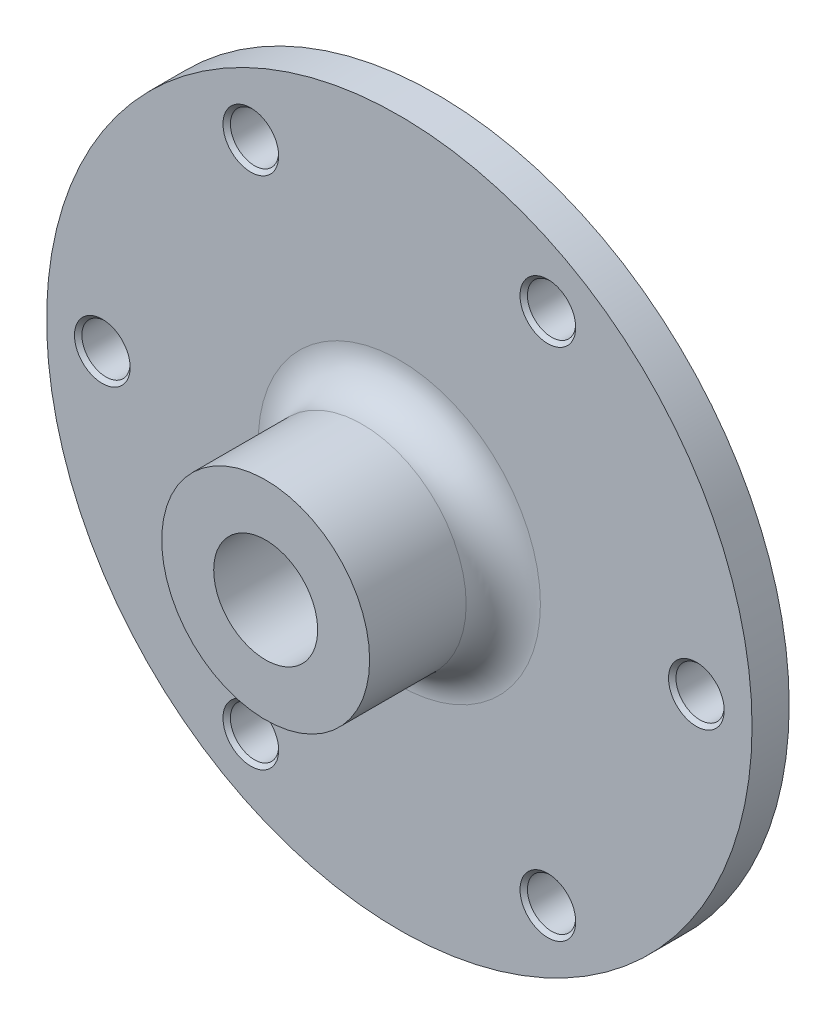
SolidWorks part; units mm, degrees
material "Plain Carbon Steel"
ref_plane "Front Plane" through (0, 0, 0) normal (0, 0, 1) x (1, 0, 0)
ref_plane "Top Plane" through (0, 0, 0) normal (0, 1, 0) x (1, 0, 0)
ref_plane "Right Plane" through (0, 0, 0) normal (1, 0, 0) x (0, 0, -1)
sketch "Sketch1" plane through (0, 0, 0) normal (0, 0, 1) x (1, 0, 0)
  circle A0 centre (0, 0) radius 47.5
  dimension "D1" = 95
extrude "Boss-Extrude1" add sketch "Sketch1" along normal mid plane 5
sketch "Sketch2" plane through (0, 0, -2.5) normal (0, 0, -1) x (-1, 0, 0)
  circle A0 centre (0, 0) radius 35
  dimension "D1" = 70
extrude "Boss-Extrude2" add sketch "Sketch2" along normal blind 5
sketch "Sketch4" plane through (0, 0, 2.5) normal (0, 0, 1) x (1, 0, 0)
  circle A0 centre (0, 0) radius 14
  dimension "D1" = 28
extrude "Boss-Extrude3" add sketch "Sketch4" along normal blind 18
hole_wizard "CSK for M12 Hex Socket Countersunk Cap Screw1" positions "Sketch6" profile "Sketch7" countersink size "M12" standard "ISO" end condition through all
sketch "Sketch6" plane through (0, 0, -7.5) normal (0, 0, -1) x (-1, 0, 0)
  point P0 (0, 0)
sketch "Sketch7" plane through (0, 0, -7.5) normal (1, 0, 0) x (0, 1, 0)
  line L0 (0, 0) -> (0, 28)
  line L1 (0, 28) -> (7, 28)
  line L2 (7, 28) -> (7, 6)
  line L3 (7, 6) -> (13, 0)
  line L5 (13, 0) -> (0, 0)
  line L6 (-7, 6) -> (-13, 0) construction
  line L11 (0, -6.35) -> (0, 107.95) construction
  dimension "Thru Hole Dia." = 14
  dimension "Thru Hole Depth" = 28
  dimension "Near C'Sink Dia." = 26
  dimension "Near C'Sink Angle" = 90
fillet "Fillet1" radius 5 1 edges at (14, 0, 2.5)
sketch "Sketch12" plane through (0, 0, 2.5) normal (0, 0, 1) x (1, 0, 0)
  circle A0 centre (0, 0) radius 40 construction
  dimension "D1" = 80
hole_wizard "CSK for M6 Hex Socket Countersunk Cap Screw1" positions "Sketch13" profile "Sketch14" countersink size "M6" standard "ISO" end condition through all
sketch "Sketch13" plane through (0, 0, 2.5) normal (0, 0, 1) x (1, 0, 0)
  circle A0 centre (0, 0) radius 40 construction
  point P0 (-40, 0)
sketch "Sketch14" plane through (-40, 0, 2.5) normal (1, 0, 0) x (0, -1, 0)
  line L0 (0, 0) -> (0, 10)
  line L1 (0, 10) -> (3.25, 10)
  line L2 (3.25, 10) -> (3.25, 0.5)
  line L3 (3.25, 0.5) -> (3.75, 0)
  line L5 (3.75, 0) -> (0, 0)
  line L6 (-3.25, 0.5) -> (-3.75, 0) construction
  line L11 (0, -6.35) -> (0, 107.95) construction
  dimension "Thru Hole Dia." = 6.5
  dimension "Thru Hole Depth" = 10
  dimension "Near C'Sink Dia." = 7.5
  dimension "Near C'Sink Angle" = 90
pattern_circular "CirPattern1" count 6 over 360 about axis through (0, 0, 0) along (0, 0, 1) of "CSK for M6 Hex Socket Countersunk Cap Screw1"
